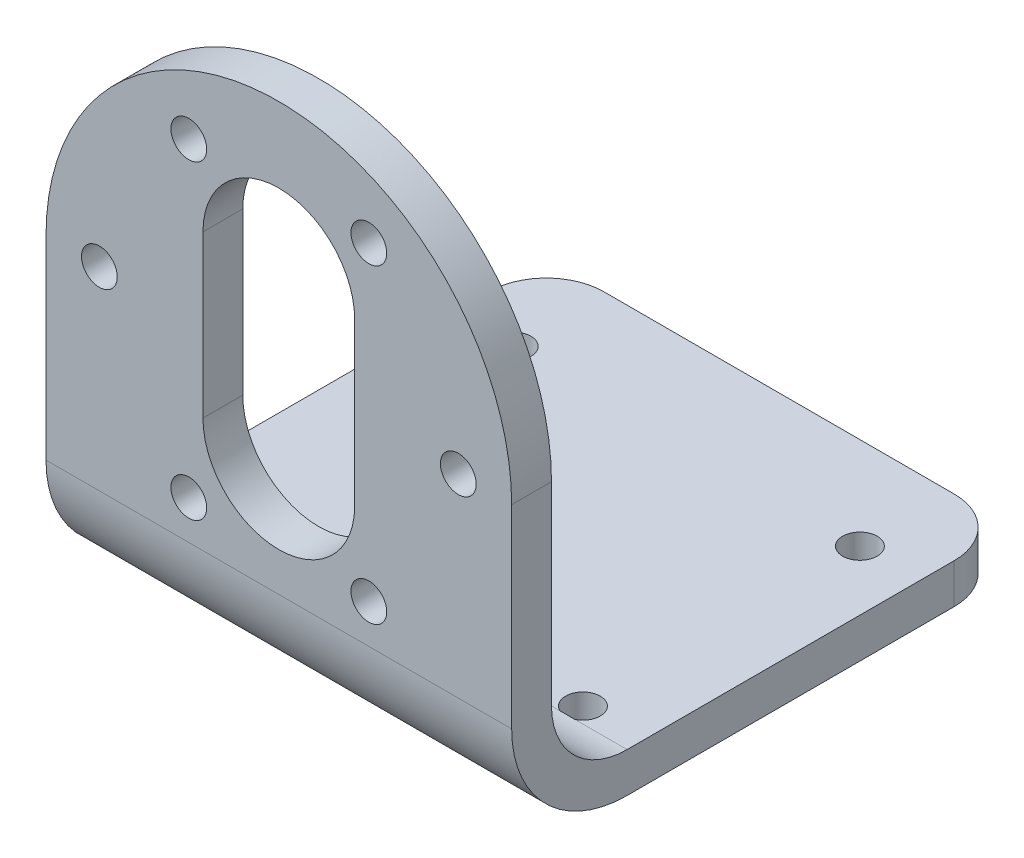
SolidWorks part; units mm, degrees
ref_plane "Front Plane" through (0, 0, 0) normal (0, 0, 1) x (1, 0, 0)
ref_plane "Top Plane" through (0, 0, 0) normal (0, 1, 0) x (1, 0, 0)
ref_plane "Right Plane" through (0, 0, 0) normal (1, 0, 0) x (0, 0, -1)
sketch "Sketch1" plane through (0, 0, 0) normal (0, 1, 0) x (1, 0, 0)
  line L1 (-47.1412, -7.433) -> (-6.7912, -7.433)
  line L2 (-47.1412, -7.433) -> (-47.1412, -50.783)
  line L3 (-47.1412, -50.783) -> (-6.7912, -50.783)
  line L4 (-6.7912, -7.433) -> (-6.7912, -50.783)
extrude "Boss-Extrude1" add sketch "Sketch1" along normal blind 47
sketch "Sketch3" plane through (0, 0, 50.783) normal (0, 0, 1) x (1, 0, 0)
  line L6 (-47.1412, 26.825) -> (-47.1412, 47)
  line L7 (-47.1412, 47) -> (-6.7912, 47)
  line L8 (-6.7912, 26.825) -> (-6.7912, 47)
  arc A1 (-6.7912, 26.825) -> (-47.1412, 26.825) centre (-26.9662, 26.825) ccw
  line M2 (-6.7912, 0) -> (-6.7912, 47)
  line M3 (-6.7912, 47) -> (-47.1412, 47)
  line M4 (-47.1412, 47) -> (-47.1412, 0)
extrude "Cut-Extrude2" cut sketch "Sketch3" against normal blind 102 contours A1 L7 M4 | A1 M2 M3
fillet "Fillet1" radius 10 1 edges at (-26.9662, 0, 50.783)
sketch "Sketch5" plane through (-47.1412, 0, 0) normal (-1, 0, 0) x (0, 0, 1)
  line L0 (7.433, 0) -> (-6.6658, 0)
  line L1 (-6.6658, 0) -> (-6.6658, 3.45)
  line L2 (50.783, 47) -> (50.783, 59.7784)
  line L3 (50.783, 59.7784) -> (47.333, 59.7784)
  line L5 (-6.6658, 3.45) -> (36.5956, 3.45)
  line L6 (-6.6658, 3.45) -> (-6.6658, 59.7784)
  line L7 (-6.6658, 59.7784) -> (47.333, 59.7784)
  line L8 (47.333, 17.5785) -> (47.333, 59.7784)
  line L9 (36.5956, 3.45) -> (40.783, 3.45)
  line L12 (47.333, 10) -> (47.333, 17.5785)
  arc A1 (40.783, 3.45) -> (47.333, 10) centre (40.783, 10) ccw
  line M2 (50.783, 26.825) -> (7.433, 26.825)
  line M3 (7.433, 26.825) -> (7.433, 0)
extrude "Cut-Extrude3" cut sketch "Sketch5" against normal blind 102 contours L8 L7 L6 L5 M2 M3 | L5 L8 M2 M3
fillet "Fillet2" radius 5 2 edges at (-6.7912, 1.725, 7.433) (-47.1412, 1.725, 7.433)
sketch "Sketch6" plane through (0, 3.45, 0) normal (0, 1, 0) x (1, 0, 0)
  line L0 (-26.9662, -7.433) -> (-26.9662, -12.0641) construction
  line L1 (-42.1412, -7.433) -> (-11.7912, -7.433) construction
  circle A0 centre (-41.9662, -15.433) radius 1.5
  circle A1 centre (-11.9662, -15.433) radius 1.5
  circle A2 centre (-41.9662, -39.433) radius 1.5
  circle A3 centre (-11.9662, -39.433) radius 1.5
  point P1 (0, 0)
  point P5 (0, 0)
  point P6 (0, 0)
  point P7 (0, 0)
  point P8 (-11.2427, -15.433)
  dimension "D1" = 30
  dimension "D2" = 24
  dimension "D3" = 8
  dimension "D4" = 3
  dimension "D5" = 15
sketch "Sketch7" plane through (0, 0, 50.783) normal (0, 0, 1) x (1, 0, 0)
  line L0 (-47.1412, 21.9829) -> (-33.5412, 21.9829)
  line L2 (-33.5412, 33.925) -> (-33.5412, 19.945)
  line L4 (-20.3912, 33.925) -> (-20.3912, 19.945)
  line L5 (-47.1412, 26.825) -> (-47.1412, 10) construction
  line L6 (-20.3912, 20.4169) -> (-6.7912, 20.4169)
  line L7 (-6.7912, 26.825) -> (-6.7912, 10) construction
  line L8 (-26.9662, 47) -> (-26.9662, 40.5)
  arc A0 (-6.7912, 26.825) -> (-47.1412, 26.825) centre (-26.9662, 26.825) ccw construction
  arc A1 (-20.3912, 33.925) -> (-33.5412, 33.925) centre (-26.9662, 33.925) ccw
  arc A2 (-33.5412, 19.945) -> (-20.3912, 19.945) centre (-26.9662, 19.945) ccw
extrude "Cut-Extrude5" cut sketch "Sketch7" against normal blind 102 contours L2 A2 L4 A1
sketch "Sketch8" plane through (0, 0, 50.783) normal (0, 0, 1) x (1, 0, 0)
  line L4 (-40.9662, 26.825) -> (-44.0662, 26.825)
  line L5 (-12.9662, 26.825) -> (-9.8662, 26.825)
  arc A0 (-33.8891, 38.9936) -> (-20.0433, 38.9936) centre (-26.9662, 26.825) ccw
  arc A1 (-35.5437, 41.6181) -> (-18.3887, 41.6181) centre (-26.9662, 26.825) ccw
  arc A2 (-20.0433, 14.6564) -> (-20.0519, 14.6448) centre (-26.9662, 19.725) cw
  arc A3 (-33.8806, 39.0052) -> (-33.8891, 38.9936) centre (-26.9662, 33.925) ccw
  circle A4 centre (-34.7662, 40.2772) radius 1.55
  circle A5 centre (-19.1662, 40.2772) radius 1.55
  circle A6 centre (-19.1662, 13.3728) radius 1.55
  arc A7 (-20.0433, 38.9936) -> (-20.0519, 39.0052) centre (-26.9662, 33.925) ccw
  circle A8 centre (-34.7662, 13.3728) radius 1.55
  arc A9 (-33.8806, 14.6448) -> (-33.8891, 14.6564) centre (-26.9662, 19.725) cw
  circle A10 centre (-42.5162, 26.825) radius 1.55
  circle A11 centre (-11.4162, 26.825) radius 1.55
extrude "Cut-Extrude6" cut sketch "Sketch8" against normal blind 102 contours A8 | A6 | L5 A11 | L5 A11 | L4 A10 | L4 A10 | A4 | A5 A4
extrude "Cut-Extrude7" cut sketch "Sketch6" against normal through all
